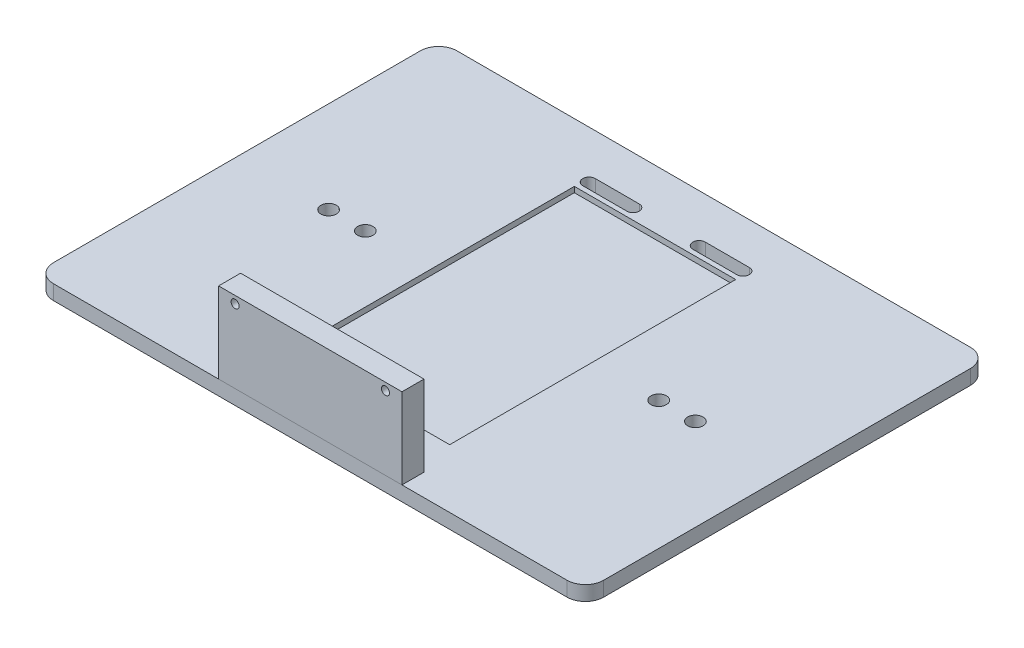
SolidWorks part; units mm, degrees
ref_plane "Front Plane" through (0, 0, 0) normal (0, 0, 1) x (1, 0, 0)
ref_plane "Top Plane" through (0, 0, 0) normal (0, 1, 0) x (1, 0, 0)
ref_plane "Right Plane" through (0, 0, 0) normal (1, 0, 0) x (0, 0, -1)
sketch "Sketch1" plane through (0, 0, 0) normal (0, 1, 0) x (1, 0, 0)
  line L0 (-75, 0) -> (75, 0) construction
  line L1 (-75, -55) -> (75, -55)
  line L2 (-75, -55) -> (-75, 55)
  line L3 (-75, 55) -> (75, 55)
  line L4 (75, -55) -> (75, 55)
  line L5 (-75, -55) -> (75, 55) construction
  line L6 (-75, 55) -> (75, -55) construction
  point P0 (0, 0)
  dimension "D1" = 150
  dimension "D2" = 110
extrude "Boss-Extrude1" add sketch "Sketch1" along normal blind 4
fillet "Fillet1" radius 5 4 edges at (-75, 2, -55) (-75, 2, 55) (75, 2, -55) (75, 2, 55)
sketch "Sketch2" plane through (0, 4, 0) normal (0, 1, 0) x (1, 0, 0)
  line L0 (-75, 0) -> (75, 0) construction
  line L1 (-75, 50) -> (-75, -50) construction
  line L2 (75, -50) -> (75, 50) construction
  line L3 (0, 55) -> (0, -55) construction
  line L4 (70, 55) -> (-70, 55) construction
  line L5 (-70, -55) -> (70, -55) construction
  circle A0 centre (-50, 0) radius 2.1
  circle A1 centre (-40, 0) radius 2.1
  point P16 (0, 0)
  point P18 (0, 0)
  dimension "D1" = 4.2
  dimension "D2" = 50
  dimension "D3" = 4.2
  dimension "D4" = 40
extrude "Cut-Extrude1" cut sketch "Sketch2" against normal through all
sketch "Sketch3" plane through (0, 0, 0) normal (0, -1, 0) x (1, 0, 0)
  line L0 (-75, 0) -> (75, 0) construction
  line L1 (-75, -50) -> (-75, 50) construction
  line L2 (75, 50) -> (75, -50) construction
  line L3 (0, 55) -> (0, -55) construction
  line L4 (-70, 55) -> (70, 55) construction
  line L5 (70, -55) -> (-70, -55) construction
  circle A0 centre (-50, 0) radius 3
  circle A1 centre (-40, 0) radius 3
  dimension "D1" = 6
  dimension "D2" = 6
extrude "Boss-Extrude2" add sketch "Sketch3" along normal blind 2
mirror "Mirror1" about plane through (0, 0, 0) normal (1, 0, 0) of "Boss-Extrude2", "Cut-Extrude1"
sketch "Sketch4" plane through (0, 4, 0) normal (0, 1, 0) x (1, 0, 0)
  line L0 (0, -55) -> (0, 55) construction
  line L1 (-22, -39) -> (-6, -39)
  line L2 (-22, -39) -> (-22, 39)
  line L3 (-22, 39) -> (22, 39)
  line L4 (22, -39) -> (22, 39)
  line L5 (-22, -39) -> (22, 39) construction
  line L6 (-22, 39) -> (22, -39) construction
  line L7 (-70, -55) -> (70, -55) construction
  line L8 (70, 55) -> (-70, 55) construction
  line L9 (6, -39) -> (22, -39)
  line L10 (-6, -43) -> (6, -43)
  line L11 (-6, -43) -> (-6, -39)
  line L13 (6, -43) -> (6, -39)
  line L14 (-6, -43) -> (6, -39) construction
  line L15 (-6, -39) -> (6, -43) construction
  point P0 (0, 0)
  point P15 (0, -41)
  dimension "D1" = 44
  dimension "D2" = 78
  dimension "D3" = 0
  dimension "D4" = 4
  dimension "D5" = 12
extrude "Cut-Extrude2" cut sketch "Sketch4" against normal blind 1.5
sketch "Sketch7" plane through (0, 0, 55) normal (0, 0, 1) x (1, 0, 0)
  line L0 (-70, 4) -> (70, 4) construction
  line L1 (-25, 4) -> (25, 4)
  line L2 (-25, 4) -> (-25, 26)
  line L3 (-25, 26) -> (25, 26)
  line L4 (25, 4) -> (25, 26)
  line L5 (-25, 4) -> (25, 26) construction
  line L6 (-25, 26) -> (25, 4) construction
  line L7 (70, 0) -> (70, 4) construction
  point P0 (0, 4)
  point P7 (0, 0)
  point P8 (0, 0)
  point P9 (0, 0)
  point P10 (0, 26)
  point P11 (0, 0)
  point P12 (0, 0)
  point P14 (0, 0)
  point P15 (0, 0)
  point P18 (0, 0)
  dimension "D1" = 50
  dimension "D2" = 22
  dimension "D3" = 45
extrude "Boss-Extrude4" add sketch "Sketch7" against normal blind 6 separate body
sketch "Sketch8" plane through (0, 0, 49) normal (0, 0, -1) x (-1, 0, 0)
  line L0 (0, 4) -> (0, 26) construction
  line L1 (25, 4) -> (-25, 4) construction
  line L2 (-25, 26) -> (25, 26) construction
  circle A0 centre (-20.5, 24) radius 1.1
  circle A1 centre (20.5, 24) radius 1.1
  dimension "D1" = 2.2
  dimension "D2" = 20.5
  dimension "D3" = 20
extrude "Cut-Extrude3" cut sketch "Sketch8" against normal through all
sketch "Sketch9" plane through (0, 0, 0) normal (0, -1, 0) x (1, 0, 0)
  line L0 (0, 55) -> (0, -55) construction
  line L1 (-70, 55) -> (70, 55) construction
  line L2 (70, -55) -> (-70, -55) construction
  line L3 (-21, -42) -> (-9, -42) construction
  line L4 (-21, -40.3) -> (-9, -40.3)
  line L5 (-21, -43.7) -> (-9, -43.7)
  line L6 (-75, 0) -> (75, 0) construction
  line L7 (-75, -50) -> (-75, 50) construction
  line L8 (75, 50) -> (75, -50) construction
  line L9 (21, -42) -> (9, -42) construction
  line L10 (21, -40.3) -> (9, -40.3)
  line L11 (21, -43.7) -> (9, -43.7)
  arc A0 (-21, -40.3) -> (-21, -43.7) centre (-21, -42) ccw
  arc A1 (-9, -43.7) -> (-9, -40.3) centre (-9, -42) ccw
  arc A2 (21, -40.3) -> (21, -43.7) centre (21, -42) cw
  arc A3 (9, -43.7) -> (9, -40.3) centre (9, -42) cw
  point P8 (-15, -42)
  point P22 (15, -42)
  dimension "D1" = 12
  dimension "D2" = 3.4
  dimension "D3" = 15
  dimension "D4" = 42
extrude "Cut-Extrude4" cut sketch "Sketch9" against normal through all
